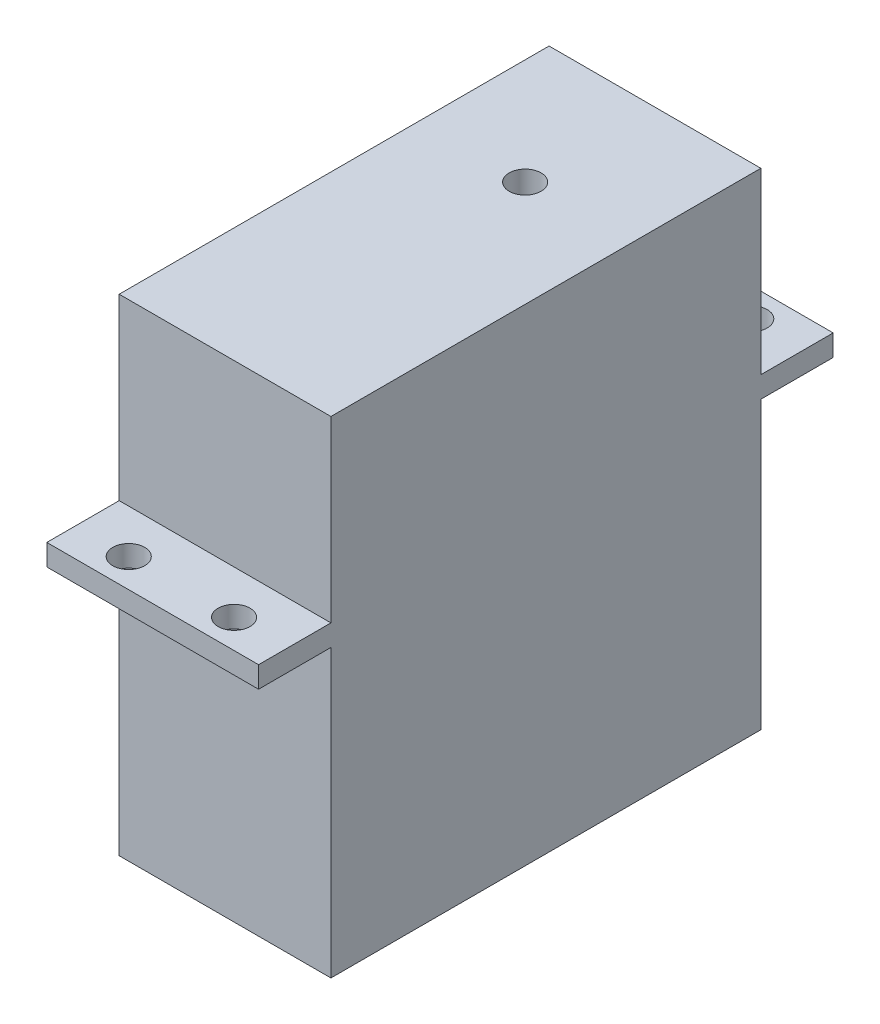
SolidWorks part; units mm, degrees
ref_plane "前视基准面" through (0, 0, 0) normal (0, 0, 1) x (1, 0, 0)
ref_plane "上视基准面" through (0, 0, 0) normal (0, 1, 0) x (1, 0, 0)
ref_plane "右视基准面" through (0, 0, 0) normal (1, 0, 0) x (0, 0, -1)
sketch "草图1" plane through (0, 0, 0) normal (0, 1, 0) x (1, 0, 0)
  line L1 (-9.95, 20.2) -> (9.95, 20.2)
  line L2 (-9.95, 20.2) -> (-9.95, -20.2)
  line L3 (-9.95, -20.2) -> (9.95, -20.2)
  line L4 (9.95, 20.2) -> (9.95, -20.2)
  line L5 (-9.95, 20.2) -> (9.95, -20.2) construction
  line L6 (-9.95, -20.2) -> (9.95, 20.2) construction
  point P0 (0, 0)
  dimension "D1" = 19.9
  dimension "D2" = 40.4
extrude "凸台-拉伸1" add sketch "草图1" along normal blind 45.7
sketch "草图2" plane through (0, 0, 0) normal (0, 0, 1) x (1, 0, 0)
  line L0 (0, 0) -> (0, 26.9) construction
  line L1 (-9.95, 0) -> (9.95, 0) construction
  line L2 (-9.95, 45.7) -> (-9.95, 0) construction
  line L3 (-9.95, 28.9) -> (9.95, 28.9)
  line L4 (-9.95, 28.9) -> (-9.95, 26.9)
  line L5 (-9.95, 26.9) -> (9.95, 26.9)
  line L6 (9.95, 28.9) -> (9.95, 26.9)
  line L7 (9.95, 45.7) -> (9.95, 0) construction
  dimension "D1" = 26.9
  dimension "D2" = 2
extrude "凸台-拉伸2" add sketch "草图2" along normal mid plane 54
sketch "草图3" plane through (0, 45.7, 0) normal (0, 1, 0) x (1, 0, 0)
  line L0 (0, -27) -> (0, 8) construction
  line L2 (9.95, -27) -> (-9.95, -27) construction
  circle A0 centre (0, 8) radius 1.5
  dimension "D2" = 3
  dimension "D1" = 35
extrude "切除-拉伸1" cut sketch "草图3" against normal blind 3
sketch "草图5" plane through (0, 28.9, 0) normal (0, 1, 0) x (1, 0, 0)
  line L3 (-4.95, 24.3) -> (4.95, 24.3) construction
  line L6 (-4.95, 24.3) -> (-4.95, -24.3) construction
  line L7 (-4.95, -24.3) -> (4.95, -24.3) construction
  line L8 (4.95, 24.3) -> (4.95, -24.3) construction
  line L9 (-4.95, 24.3) -> (4.95, -24.3) construction
  line L10 (-4.95, -24.3) -> (4.95, 24.3) construction
  circle A2 centre (-4.95, 24.3) radius 1.5
  circle A3 centre (4.95, 24.3) radius 1.5
  circle A4 centre (-4.95, -24.3) radius 1.5
  circle A5 centre (4.95, -24.3) radius 1.5
  point P0 (0, 0)
  dimension "D1" = 9.9
  dimension "D2" = 48.6
  dimension "D3" = 3
  dimension "D4" = 3
  dimension "D5" = 3
  dimension "D6" = 3
extrude "切除-拉伸2" cut sketch "草图5" against normal through all
